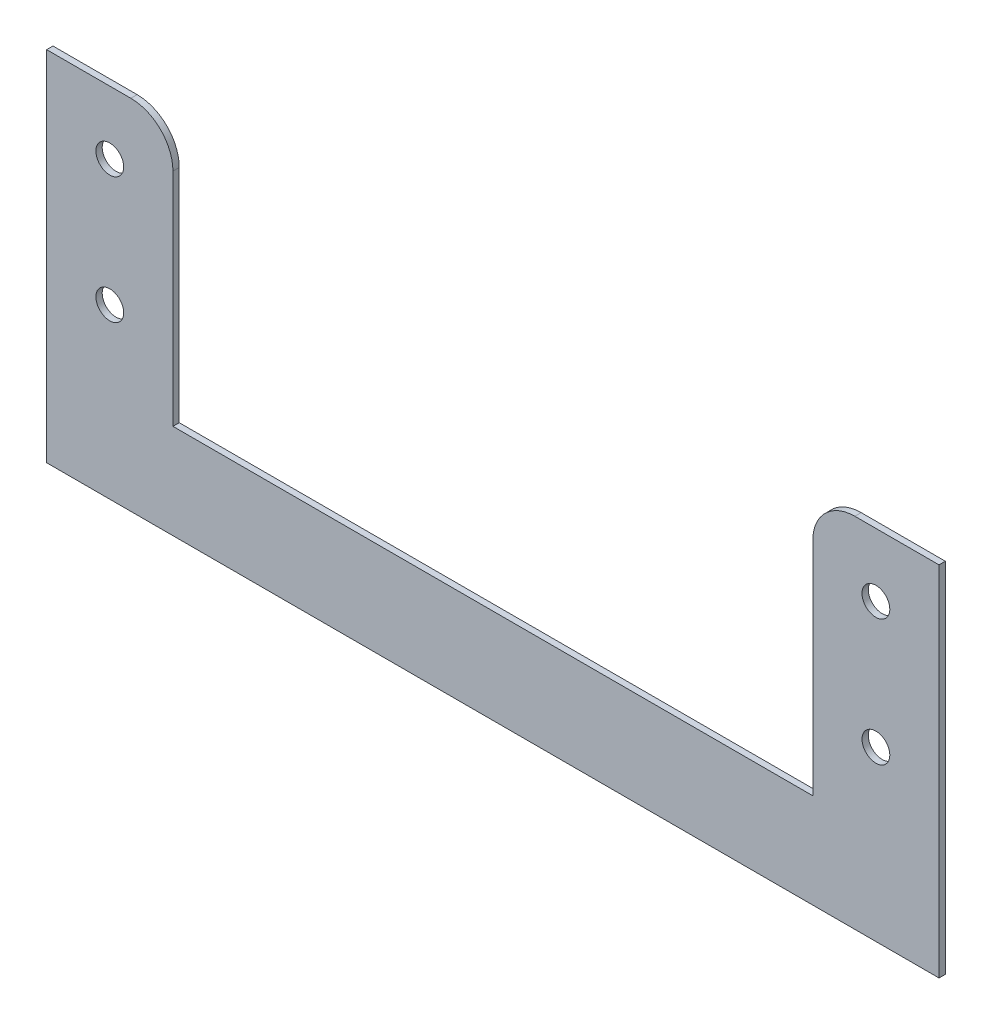
SolidWorks part; units mm, degrees
material "AISI 304"
ref_plane "Спереди" through (0, 0, 0) normal (0, 0, 1) x (1, 0, 0)
ref_plane "Сверху" through (0, 0, 0) normal (0, 1, 0) x (1, 0, 0)
ref_plane "Справа" through (0, 0, 0) normal (1, 0, 0) x (0, 0, -1)
sketch "Эскиз1" plane through (0, 0, 0) normal (0, 0, 1) x (1, 0, 0)
  line L0 (152, 0) -> (-152, 0)
  line L1 (-152, 0) -> (-152, 125)
  line L2 (-152, 125) -> (-212, 125)
  line L3 (-212, 125) -> (-212, -45)
  line L4 (-212, -45) -> (212, -45)
  line L5 (0, -1.65) -> (0, 1.65) construction
  line L6 (212, 125) -> (212, -45)
  line L7 (152, 125) -> (212, 125)
  line L8 (152, 0) -> (152, 125)
  line L9 (-182, 125) -> (-182, 35) construction
  circle A0 centre (-182, 95) radius 6.6
  circle A1 centre (-182, 35) radius 6.6
  circle A2 centre (182, 35) radius 6.6
  circle A3 centre (182, 95) radius 6.6
  point P10 (0, -45)
  point P11 (0, 0)
  dimension "D5" = 13.2
  dimension "D6" = 30
  dimension "D7" = 60
  dimension "D1" = 60
  dimension "D2" = 424
  dimension "D3" = 45
  dimension "D4" = 125
  dimension "D8" = 30
extrude "Бобышка-Вытянуть1" add sketch "Эскиз1" along normal blind 3
fillet "Скругление1" radius 20 2 edges at (152, 125, 1.5) (-152, 125, 1.5)
